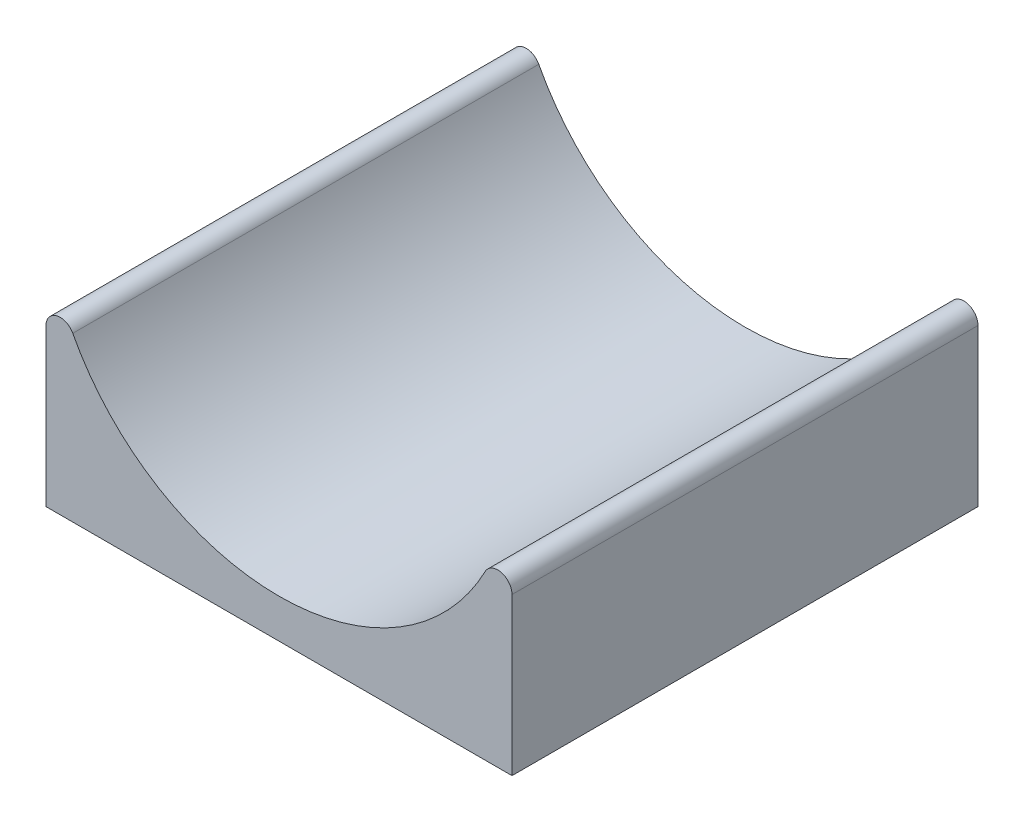
SolidWorks part; units mm, degrees
ref_plane "Front Plane" through (0, 0, 0) normal (0, 0, 1) x (1, 0, 0)
ref_plane "Top Plane" through (0, 0, 0) normal (0, 1, 0) x (1, 0, 0)
ref_plane "Right Plane" through (0, 0, 0) normal (1, 0, 0) x (0, 0, -1)
sketch "Sketch1" plane through (0, 0, 0) normal (0, 0, 1) x (1, 0, 0)
  line L0 (-20.828, -10.2862) -> (-20.828, -24.3086)
  line L1 (-20.828, -24.3086) -> (20.828, -24.3086)
  line L2 (20.828, -24.3086) -> (20.828, -10.2862)
  arc A0 (-18.434, -9.6951) -> (18.434, -9.6951) centre (0, 0) ccw
  arc A1 (-20.828, -10.2862) -> (-18.434, -9.6951) centre (-19.558, -10.2862) cw
  arc A2 (20.828, -10.2862) -> (18.434, -9.6951) centre (19.558, -10.2862) ccw
  point P8 (-20.828, 0)
  point P11 (20.828, 0)
  dimension "D1" = 1.27
  dimension "D2" = 1.27
extrude "Boss-Extrude1" add sketch "Sketch1" along normal blind 41.656
